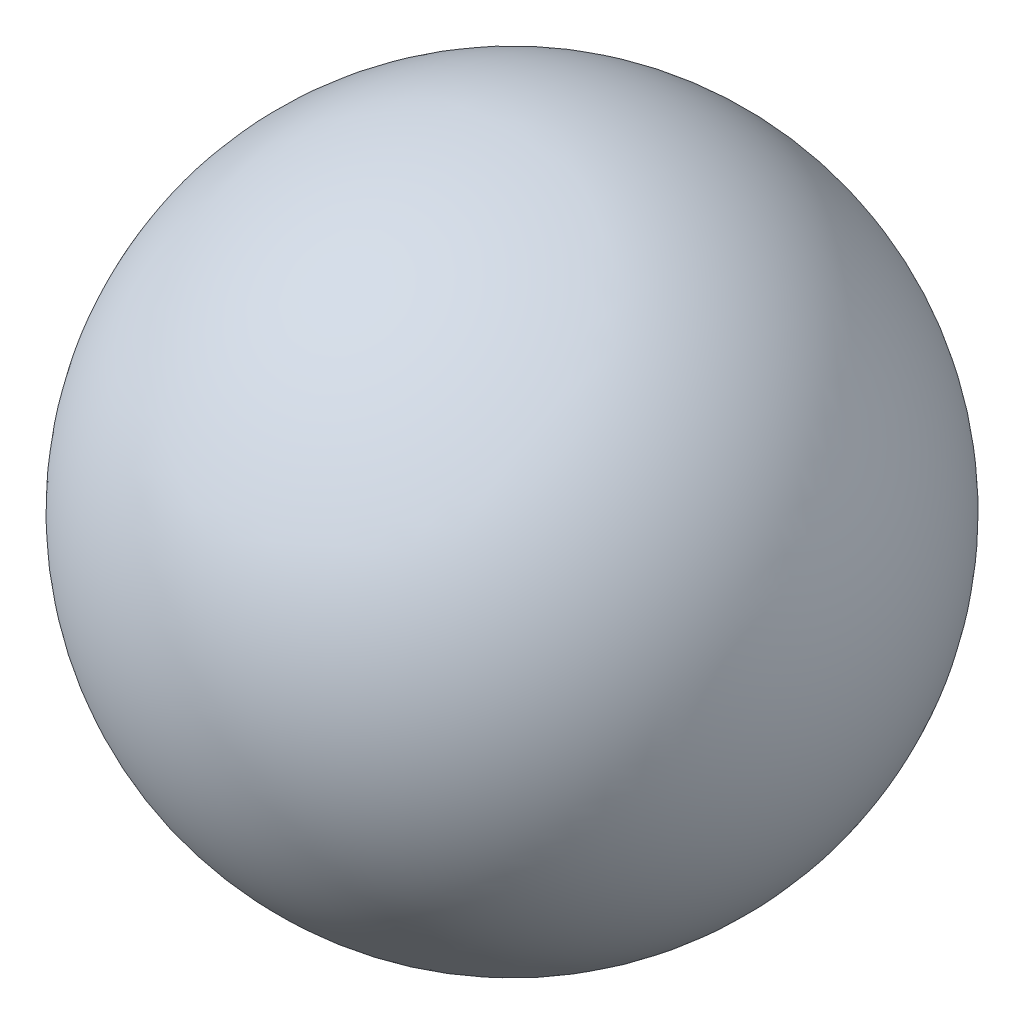
SolidWorks part; units mm, degrees
material "AISI 347, ricotto (SS)"
ref_plane "Piano frontale" through (0, 0, 0) normal (0, 0, 1) x (1, 0, 0)
ref_plane "Piano superiore" through (0, 0, 0) normal (0, 1, 0) x (1, 0, 0)
ref_plane "Piano destro" through (0, 0, 0) normal (1, 0, 0) x (0, 0, -1)
sketch "Schizzo1" plane through (0, 0, 0) normal (0, 0, 1) x (1, 0, 0)
  line L0 (-3.9799, 0.4001) -> (3.9799, -0.4001)
  arc A0 (3.9799, -0.4001) -> (-3.9799, 0.4001) centre (0, 0) ccw
revolve "Rivoluzione1" add sketch "Schizzo1" angle 360 about L0
